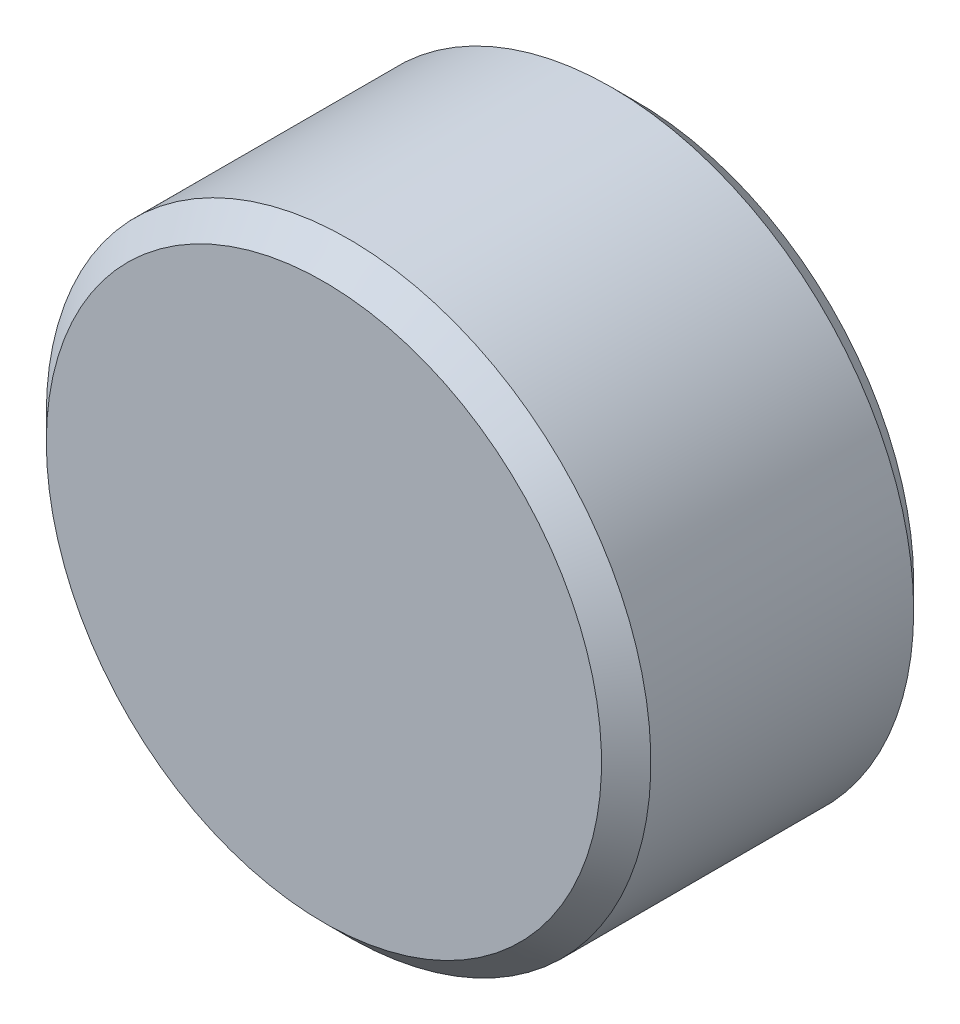
SolidWorks part; units mm, degrees
material "Delrin 2700 NC010, Low Viscosity Acetal Copolymer (SS)"
ref_plane "Front Plane" through (0, 0, 0) normal (0, 0, 1) x (1, 0, 0)
ref_plane "Top Plane" through (0, 0, 0) normal (0, 1, 0) x (1, 0, 0)
ref_plane "Right Plane" through (0, 0, 0) normal (1, 0, 0) x (0, 0, -1)
sketch "Sketch1" plane through (0, 0, 0) normal (0, 0, 1) x (1, 0, 0)
  circle A0 centre (0, 0) radius 6.223
  dimension "D1" = 12.446
extrude "Boss-Extrude1" add sketch "Sketch1" along normal blind 6.4262
chamfer "Chamfer1" distance 0.508 angle 45
